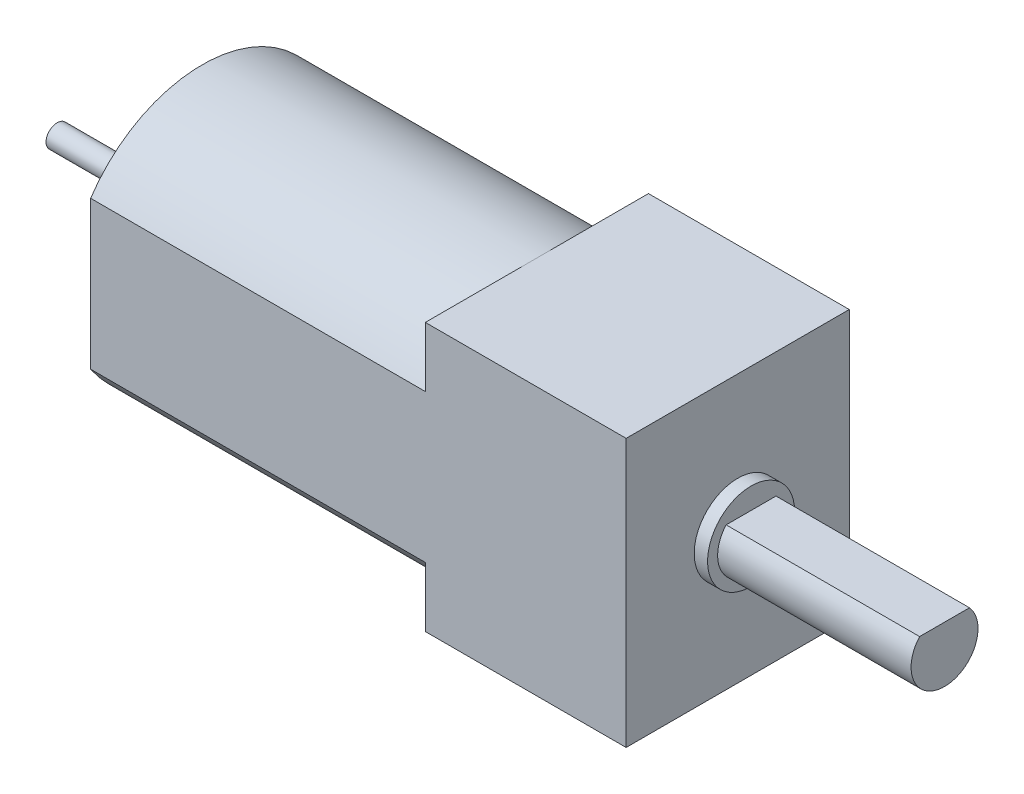
SolidWorks part; units mm, degrees
ref_plane "Plan de face" through (0, 0, 0) normal (0, 0, 1) x (1, 0, 0)
ref_plane "Plan de dessus" through (0, 0, 0) normal (0, 1, 0) x (1, 0, 0)
ref_plane "Plan de droite" through (0, 0, 0) normal (1, 0, 0) x (0, 0, -1)
sketch "Esquisse1" plane through (0, 0, 0) normal (1, 0, 0) x (0, 0, -1)
  line L0 (-5, 3.3166) -> (-5, -3.3166)
  line L1 (5, 3.3166) -> (5, -3.3166)
  circle A0 centre (0, 0) radius 6 construction
  arc A1 (-5, -3.3166) -> (5, -3.3166) centre (0, 0) ccw
  arc A2 (-5, 3.3166) -> (5, 3.3166) centre (0, 0) cw
  dimension "D1" = 12
  dimension "D2" = 10
  dimension "D3" = 5
extrude "Boss.-Extru.1" add sketch "Esquisse1" along normal blind 15
sketch "Esquisse2" plane through (0, 0, 0) normal (-1, 0, 0) x (0, 0, 1)
  circle A0 centre (0, 0) radius 2.5
  dimension "D1" = 5
extrude "Boss.-Extru.2" add sketch "Esquisse2" along normal blind 2
sketch "Esquisse3" plane through (15, 0, 0) normal (1, 0, 0) x (0, 0, -1)
  line L0 (-5, 3.3166) -> (-5, -3.3166) construction
  line L1 (-5, 6) -> (5, 6)
  line L2 (-5, 6) -> (-5, -6)
  line L3 (-5, -6) -> (5, -6)
  line L4 (5, 6) -> (5, -6)
  line L5 (5, -3.3166) -> (5, 3.3166) construction
  line L6 (5, 0) -> (-5, 0) construction
  arc A0 (5, 3.3166) -> (-5, 3.3166) centre (0, 0) ccw construction
  arc A1 (-5, -3.3166) -> (5, -3.3166) centre (0, 0) ccw construction
extrude "Boss.-Extru.3" add sketch "Esquisse3" along normal blind 9
sketch "Esquisse4" plane through (24, 0, 0) normal (1, 0, 0) x (0, 0, -1)
  circle A0 centre (0, 0) radius 1.95
  dimension "D1" = 3.9
extrude "Boss.-Extru.4" add sketch "Esquisse4" along normal blind 0.6
sketch "Esquisse5" plane through (24.6, 0, 0) normal (1, 0, 0) x (0, 0, -1)
  circle A0 centre (0, 0) radius 1.5
  dimension "D1" = 3
extrude "Boss.-Extru.5" add sketch "Esquisse5" along normal blind 8.67
sketch "Esquisse6" plane through (33.27, 0, 0) normal (1, 0, 0) x (0, 0, -1)
  line L0 (-1.118, 1) -> (1.118, 1)
  circle A0 centre (0, 0) radius 1.5 construction
  arc A1 (-1.118, 1) -> (1.118, 1) centre (0, 0) cw
  dimension "D1" = 1
extrude "Enlèv. mat.-Extru.1" cut sketch "Esquisse6" against normal up to surface (8.67 mm away) up to face at (24.6, 0, -1.95)
sketch "Esquisse7" plane through (-2, 0, 0) normal (-1, 0, 0) x (0, 0, 1)
  circle A0 centre (0, 0) radius 0.5
  dimension "D1" = 1
extrude "Boss.-Extru.6" add sketch "Esquisse7" along normal blind 4.5
